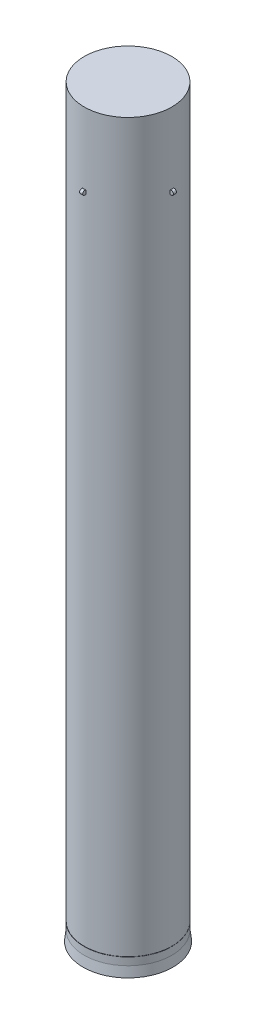
SolidWorks part; units mm, degrees
ref_plane "Front Plane" through (0, 0, 0) normal (0, 0, 1) x (1, 0, 0)
ref_plane "Top Plane" through (0, 0, 0) normal (0, 1, 0) x (1, 0, 0)
ref_plane "Right Plane" through (0, 0, 0) normal (1, 0, 0) x (0, 0, -1)
sketch "Sketch1" plane through (0, 0, 0) normal (0, 0, 1) x (1, 0, 0)
  line L0 (0, 0) -> (0, 76500) construction
  line L1 (0, 76500) -> (4500, 76500)
  line L2 (4500, 76500) -> (4500, 1000)
  line L3 (4500, 1000) -> (4620, 0)
  line L4 (4620, 0) -> (4300, 0)
  line L5 (4300, 0) -> (4300, 1500)
  line L6 (4300, 1500) -> (4300, 73000)
  line L7 (4300, 73000) -> (0, 75000)
  line L8 (0, 75000) -> (0, 76500)
revolve "Revolve1" add sketch "Sketch1" angle 360 about L0
sketch "Sketch2" plane through (0, 0, 0) normal (0, 0, 1) x (1, 0, 0)
  line L0 (0, 0) -> (0, 76500) construction
  line L1 (4500, 76500) -> (-4500, 76500) construction
  circle A0 centre (4506, 1800) radius 10
revolve "Revolve2" add sketch "Sketch2" angle 360 about L0
sketch "Sketch3" plane through (0, 0, 0) normal (0, 0, 1) x (1, 0, 0)
  line L0 (0, 0) -> (0, 76500) construction
  line L1 (4500, 76500) -> (-4500, 76500) construction
  line L2 (0, 45000) -> (3650, 41350)
  line L3 (3650, 41350) -> (4300, 41700)
  line L4 (4300, 41700) -> (0, 45000)
  line L5 (0, 4500) -> (3650, 1698.8372)
  line L6 (3650, 1698.8372) -> (4300, 1100)
  line L7 (4300, 1100) -> (0, 4500)
sketch "Sketch4" plane through (0, 0, 0) normal (0, 0, 1) x (1, 0, 0)
  line L0 (0, 0) -> (0, 76500) construction
  line L1 (0, 74000) -> (0, 2500)
  line L2 (0, 2500) -> (420, 2500)
  line L3 (420, 2500) -> (0, 74000)
  line L4 (0, 74000) -> (480, 74000)
sketch "Sketch5" plane through (0, 0, 0) normal (0, 0, 1) x (1, 0, 0)
  line L0 (0, 0) -> (0, 4500) construction
  line L1 (0, 2250) -> (0, 0)
  line L2 (0, 0) -> (580, -450)
  line L3 (580, -450) -> (0, 2250)
  line L4 (0, 2250) -> (0, 3000)
  line L5 (420, 2500) -> (2920, 0)
  line L6 (-4620, 0) -> (4620, 0) construction
  line L7 (2920, 0) -> (2350, -450)
  line L8 (2350, -450) -> (2350, 2500)
  line L9 (2350, 2500) -> (1600, 2600)
  line L10 (2350, 2500) -> (4261.7647, 0)
  line L11 (4261.7647, 0) -> (4150, -450)
  line L12 (4150, -450) -> (2350, 2500)
  line L13 (2350, 2500) -> (3250, 2400)
sketch "Sketch6" plane through (0, 0, 0) normal (0, 0, 1) x (1, 0, 0)
  circle A0 centre (4600, 69000) radius 220
extrude "Boss-Extrude1" add sketch "Sketch6" along normal mid plane 320
sketch "Sketch7" plane through (0, 0, 0) normal (0, 0, 1) x (1, 0, 0)
  line L0 (4800, 70600) -> (5250, 70600)
  line L1 (5250, 70600) -> (5250, 71050)
  line L2 (5250, 71050) -> (4800, 71050)
  line L3 (4800, 71050) -> (4800, 70600)
  line L4 (4800, 71050) -> (5250, 71050)
  line L5 (5250, 71050) -> (5250, 71700)
  line L6 (5250, 71700) -> (4800, 71700)
  line L7 (4800, 71700) -> (4800, 71050)
  line L8 (4800, 71700) -> (5250, 71700)
  line L9 (5250, 71700) -> (5250, 72350)
  line L10 (5250, 72350) -> (4800, 72350)
  line L11 (4800, 72350) -> (4800, 71700)
  line L12 (4800, 72350) -> (5250, 72350)
  line L13 (5250, 72350) -> (5250, 73000)
  line L14 (5250, 73000) -> (4800, 73000)
  line L15 (4800, 73000) -> (4800, 72350)
  line L16 (5250, 70600) -> (5900, 70600)
  line L17 (5900, 70600) -> (5900, 71050)
  line L18 (5900, 71050) -> (5250, 71050)
  line L19 (5250, 71050) -> (5250, 70600)
  line L20 (5250, 71050) -> (5900, 71050)
  line L21 (5900, 71050) -> (5250, 71700)
  line L22 (5250, 71700) -> (5450, 71700)
  line L23 (5450, 71700) -> (5250, 71050)
  line L24 (5450, 71700) -> (5900, 71900)
  line L25 (5900, 71900) -> (5900, 72350)
  line L26 (5900, 72350) -> (5250, 72350)
  line L27 (5250, 72350) -> (5450, 71700)
  line L28 (5250, 72350) -> (5900, 72350)
  line L29 (5900, 72350) -> (5250, 73000)
  line L30 (5250, 73000) -> (5450, 73000)
  line L31 (5450, 73000) -> (5250, 72350)
  line L32 (5900, 70600) -> (6550, 70600)
  line L33 (6550, 70600) -> (6550, 71050)
  line L34 (6550, 71050) -> (5900, 71050)
  line L35 (5900, 71050) -> (5900, 70600)
  line L36 (5900, 71050) -> (6550, 71050)
  line L37 (6550, 71050) -> (6550, 71700)
  line L38 (6550, 71700) -> (5900, 71900)
  line L39 (5900, 71900) -> (5900, 71050)
  line L40 (5900, 71900) -> (6550, 71700)
  line L41 (6550, 71700) -> (5900, 72350)
  line L42 (5900, 72350) -> (6100, 72350)
  line L43 (6100, 72350) -> (5900, 71900)
  line L44 (6100, 72350) -> (6550, 72550)
  line L45 (6550, 72550) -> (6550, 73000)
  line L46 (6550, 73000) -> (6100, 73000)
  line L47 (6100, 73000) -> (6100, 72350)
  line L48 (6550, 70600) -> (7200, 70600)
  line L49 (7200, 70600) -> (7200, 71050)
  line L50 (7200, 71050) -> (6550, 71050)
  line L51 (6550, 71050) -> (6550, 70600)
  line L52 (6550, 71050) -> (7200, 71050)
  line L53 (7200, 71050) -> (6550, 71700)
  line L54 (6550, 71700) -> (6750, 71700)
  line L55 (6750, 71700) -> (6550, 71050)
  line L56 (6750, 71700) -> (7200, 71900)
  line L57 (7200, 71900) -> (7200, 72350)
  line L58 (7200, 72350) -> (6550, 72550)
  line L59 (6550, 72550) -> (6750, 71700)
  line L60 (6550, 72550) -> (7200, 72350)
  line L61 (7200, 72350) -> (6550, 73000)
  line L62 (6550, 73000) -> (6750, 73000)
  line L63 (6750, 73000) -> (6550, 72550)
pattern_circular "CirPattern1" count 4 over 360 about axis through (0, 0, 0) along (0, 1, 0) of "Boss-Extrude1"
